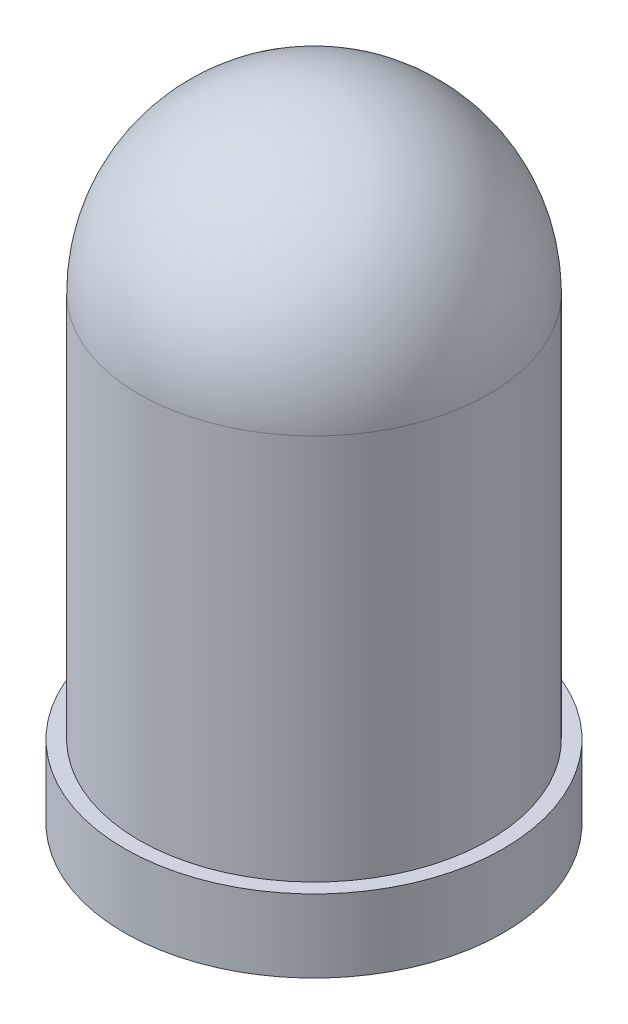
SolidWorks part; units mm, degrees
ref_plane "Front Plane" through (0, 0, 0) normal (0, 0, 1) x (1, 0, 0)
ref_plane "Top Plane" through (0, 0, 0) normal (0, 1, 0) x (1, 0, 0)
ref_plane "Right Plane" through (0, 0, 0) normal (1, 0, 0) x (0, 0, -1)
sketch "Sketch1" plane through (0, 0, 0) normal (0, 1, 0) x (1, 0, 0)
  circle A0 centre (0, 0) radius 2.4
  dimension "D1" = 4.8
extrude "Boss-Extrude1" add sketch "Sketch1" along normal blind 8.7
fillet "Fillet1" radius 2.4 1 edges at (0, 8.7, 2.4)
sketch "Sketch2" plane through (0, 0, 0) normal (0, 1, 0) x (1, 0, 0)
  circle A0 centre (0, 0) radius 2.6
  dimension "D1" = 5.2
extrude "Boss-Extrude2" add sketch "Sketch2" along normal blind 1
